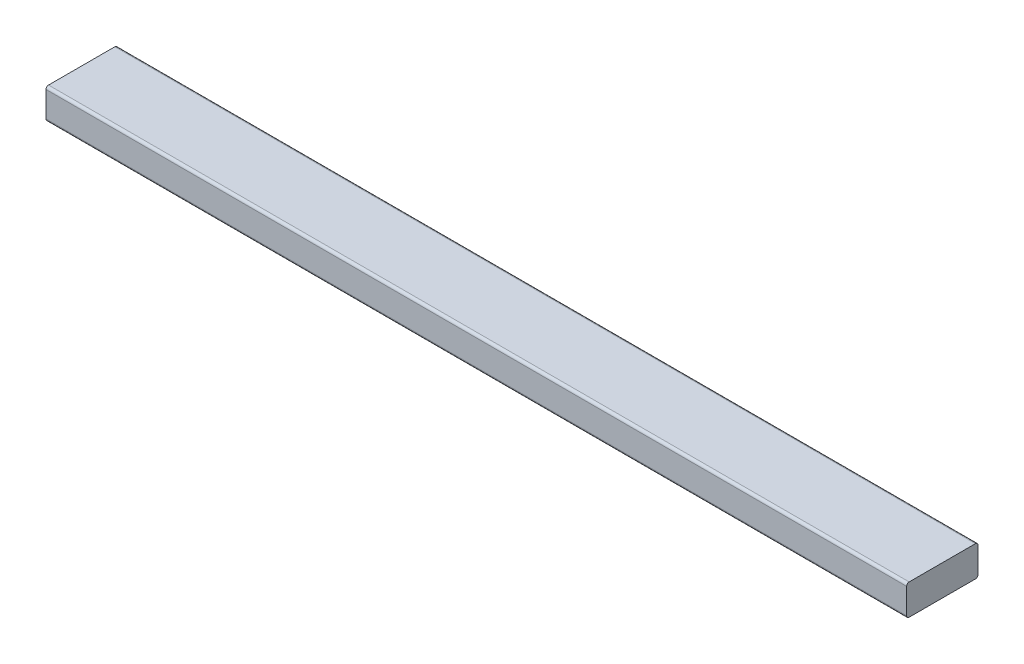
SolidWorks part; units mm, degrees
material "Pine"
ref_plane "Front Plane" through (0, 0, 0) normal (0, 0, 1) x (1, 0, 0)
ref_plane "Top Plane" through (0, 0, 0) normal (0, 1, 0) x (1, 0, 0)
ref_plane "Right Plane" through (0, 0, 0) normal (1, 0, 0) x (0, 0, -1)
sketch "Sketch1" plane through (0, 0, 0) normal (0, 0, 1) x (1, 0, 0)
  line L1 (-535.7812, 38.1) -> (535.7812, 38.1)
  line L2 (-535.7812, 38.1) -> (-535.7812, 0)
  line L3 (-535.7812, 0) -> (535.7812, 0)
  line L4 (535.7812, 38.1) -> (535.7812, 0)
  point P4 (0, 0)
  dimension "D1" = 1071.5625
  dimension "D2" = 38.1
extrude "Boss-Extrude1" add sketch "Sketch1" along normal blind 88.9
fillet "Fillet1" radius 3.175 4 edges at (0, 0, 0) (0, 0, 88.9) (0, 38.1, 0) (0, 38.1, 88.9)
